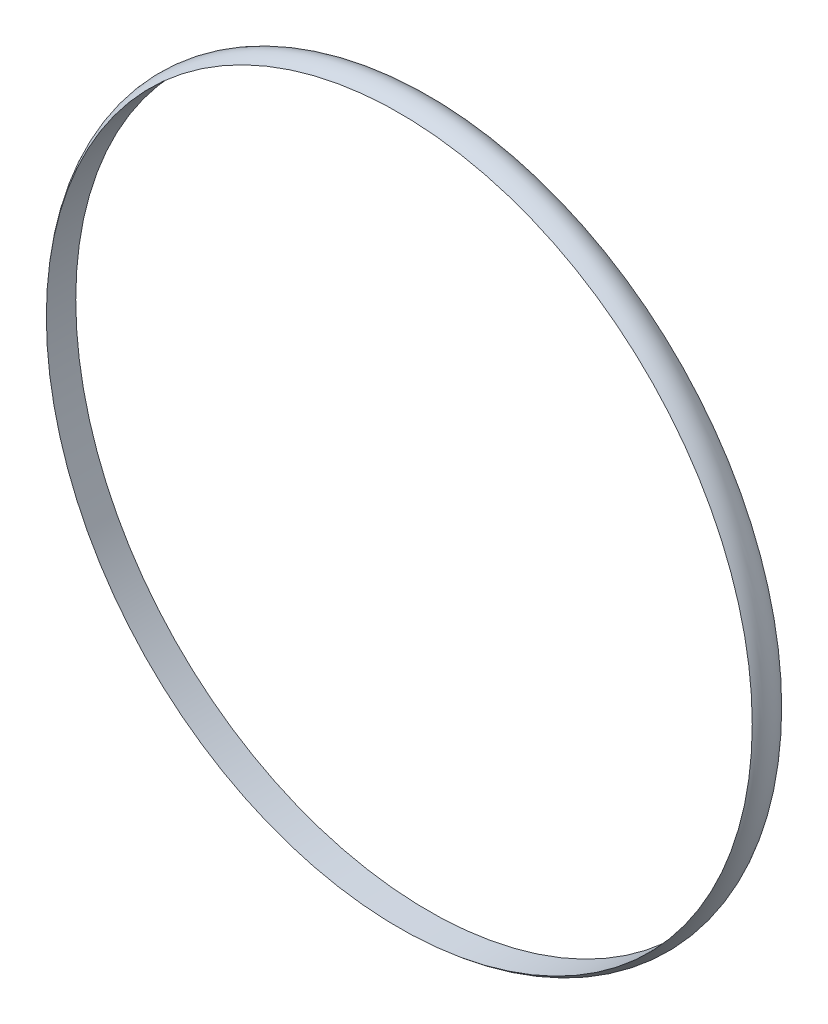
SolidWorks part; units mm, degrees
material "POLYURETHANE (11671)"
ref_plane "Front Plane" through (0, 0, 0) normal (0, 0, 1) x (1, 0, 0)
ref_plane "Top Plane" through (0, 0, 0) normal (0, 1, 0) x (1, 0, 0)
ref_plane "Right Plane" through (0, 0, 0) normal (1, 0, 0) x (0, 0, -1)
sketch "Sketch1" plane through (0, 0, 0) normal (1, 0, 0) x (0, 0, -1)
  line L0 (-4.8, 115.22) -> (4.8, 115.22)
  line L1 (0, 115.22) -> (0, 0)
  line L2 (-12.4444, 0) -> (15.3593, 0)
  arc A0 (-4.8, 115.22) -> (4.8, 115.22) centre (0, 110.32) cw
  dimension "D1" = 9.6
revolve "Revolve1" add sketch "Sketch1" angle 360 about L2
